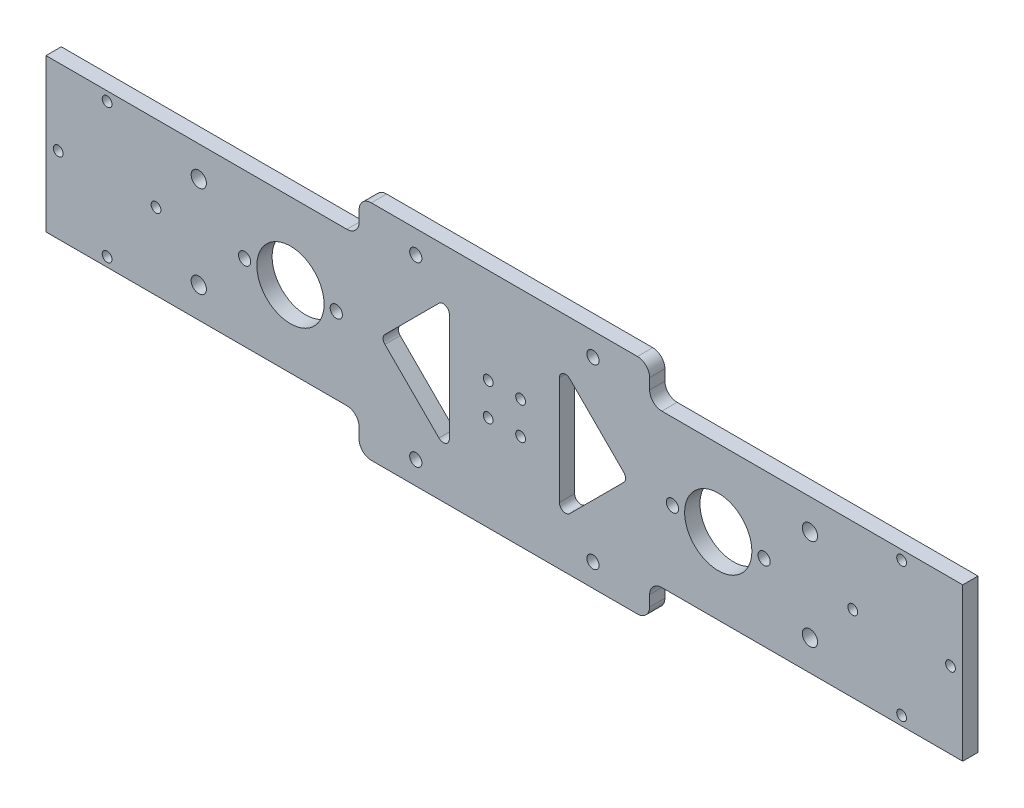
SolidWorks part; units mm, degrees
ref_plane "前视基准面" through (0, 0, 0) normal (0, 0, 1) x (1, 0, 0)
ref_plane "上视基准面" through (0, 0, 0) normal (0, 1, 0) x (1, 0, 0)
ref_plane "右视基准面" through (0, 0, 0) normal (1, 0, 0) x (0, 0, -1)
ref_plane "基准面1" through (0, 0, 0) normal (0, 0, -1) x (-1, 0, 0)
sketch "草图1" plane through (0, 0, 0) normal (0, 0, -1) x (-1, 0, 0)
  line L0 (-26.5, -36.5) -> (26.5, -36.5)
  line L1 (47.5416, -25) -> (150, -25)
  line L2 (150, -25) -> (150, 25)
  line L3 (150, 25) -> (47.5416, 25)
  line L4 (26.5, 36.5) -> (-26.5, 36.5)
  line L5 (-47.5416, 25) -> (-150, 25)
  line L6 (-150, 25) -> (-150, -25)
  line L7 (-150, -25) -> (-47.5416, -25)
  circle A0 centre (-29, 29) radius 2.1
  circle A1 centre (-29, -29) radius 2.1
  circle A2 centre (29, -29) radius 2.1
  circle A3 centre (29, 29) radius 2.1
  arc A4 (-47.5416, -25) -> (-34.9167, -31.9) centre (-47.5416, -40) cw
  arc A5 (-34.9167, -31.9) -> (-26.5, -36.5) centre (-26.5, -26.5) ccw
  arc A6 (26.5, -36.5) -> (34.9167, -31.9) centre (26.5, -26.5) ccw
  arc A7 (34.9167, -31.9) -> (47.5416, -25) centre (47.5416, -40) cw
  arc A8 (47.5416, 25) -> (34.9167, 31.9) centre (47.5416, 40) cw
  arc A9 (34.9167, 31.9) -> (26.5, 36.5) centre (26.5, 26.5) ccw
  arc A10 (-26.5, 36.5) -> (-34.9167, 31.9) centre (-26.5, 26.5) ccw
  arc A11 (-34.9167, 31.9) -> (-47.5416, 25) centre (-47.5416, 40) cw
  circle A12 centre (-54.5, 0) radius 2.1
  circle A13 centre (-114, 0) radius 1.6
  circle A14 centre (-5.3033, 5.3033) radius 1.6
  circle A15 centre (5.3033, 5.3033) radius 1.6
  circle A16 centre (70, 0) radius 11
  circle A17 centre (-85.5, 0) radius 2.1
  circle A18 centre (85.5, 0) radius 2.1
  circle A19 centre (54.5, 0) radius 2.1
  circle A20 centre (-70, 0) radius 11
  circle A21 centre (5.3033, -5.3033) radius 1.6
  circle A22 centre (-5.3033, -5.3033) radius 1.6
  circle A23 centre (114, 0) radius 1.6
  circle A24 centre (146, 0) radius 1.6
  circle A25 centre (130, 22) radius 1.6
  circle A26 centre (130, -22) radius 1.6
  circle A27 centre (-130, -22) radius 1.6
  circle A28 centre (-130, 22) radius 1.6
  circle A29 centre (-146, 0) radius 1.6
  circle A30 centre (100, 15) radius 2.5
  circle A31 centre (-100, 15) radius 2.5
  circle A32 centre (-100, -15) radius 2.5
  circle A33 centre (100, -15) radius 2.5
extrude "凸台-拉伸1" add sketch "草图1" against normal blind 5
sketch "草图2" plane through (0, 0, 5) normal (0, 0, 1) x (1, 0, 0)
  circle A0 centre (-85.5, 0) radius 3.6895
  circle A1 centre (-54.5, 0) radius 3.294
extrude "凸台-拉伸2" add sketch "草图2" against normal blind 5
sketch "草图3" plane through (0, 0, 5) normal (0, 0, 1) x (1, 0, 0)
  circle A0 centre (-85, 0) radius 2
  circle A1 centre (-55, 0) radius 2
  circle A2 centre (-70, 0) radius 11 construction
  dimension "D1" = 15
  dimension "D2" = 15
  dimension "D3" = 4
  dimension "D4" = 4
extrude "切除-拉伸1" cut sketch "草图3" against normal up to next
ref_plane "基准面2" through (0, 0, 0) normal (-1, 0, 0) x (0, 0, 1)
mirror "镜向1" about plane through (0, 0, 0) normal (-1, 0, 0) of "凸台-拉伸2", "切除-拉伸1"
sketch "草图4" plane through (0, 0, 0) normal (0, 0, -1) x (-1, 0, 0)
  circle A0 centre (28.9914, -28.9914) radius 2
  circle A1 centre (-28.9914, 28.9914) radius 2
  circle A4 centre (28.9914, 28.9914) radius 2
  circle A5 centre (-28.9914, -28.9914) radius 2
  point P0 (0, 0)
  point P2 (0, 0)
  dimension "D1" = 4
  dimension "D2" = 4
  dimension "D3" = 4
  dimension "D4" = 4
  dimension "D6" = 41
  dimension "D7" = 41
  dimension "D8" = 41
  dimension "D5" = 41
sketch "草图5" plane through (0, 0, 0) normal (0, 0, -1) x (-1, 0, 0)
  line L0 (26.5, 36.5) -> (-26.5, 36.5) construction
  line L2 (47.5416, 25) -> (47.5416, 36.5)
  line L3 (47.5416, 36.5) -> (21.5189, 36.5)
  line L5 (47.5416, -25) -> (150, -25) construction
  line L7 (-47.5416, 25) -> (-47.5416, 36.5)
  line L8 (-47.5416, 36.5) -> (21.5189, 36.5)
  line L11 (-47.5416, 25) -> (-47.5416, -25)
  line L13 (47.5416, 25) -> (47.5416, -25)
  line L15 (26.5, -36.5) -> (47.5416, -36.5)
  line L18 (47.5416, -36.5) -> (47.5416, -25)
  line L19 (26.5, -36.5) -> (-47.5416, -36.5)
  line L22 (-47.5416, -36.5) -> (-47.5416, -25)
  line L23 (-14.0612, 16.4225) -> (11.4339, 16.4225)
  line L24 (-14.0612, 16.4225) -> (-14.0612, -16.9967)
  line L25 (-14.0612, -16.9967) -> (11.4339, -16.9967)
  line L26 (11.4339, 16.4225) -> (11.4339, -16.9967)
  arc A0 (47.5416, -25) -> (34.9167, -31.9) centre (47.5416, -40) ccw construction
extrude "凸台-拉伸3" add sketch "草图5" against normal blind 5
extrude "切除-拉伸2" cut sketch "草图4" against normal up to next
fillet "圆角1" radius 4 8 edges at (47.5416, -25, 2.5) (47.5416, -36.5, 2.5) (-47.5416, -36.5, 2.5) (-47.5416, -25, 2.5) (-47.5416, 25, 2.5) (-47.5416, 36.5, 2.5) (47.5416, 25, 2.5) (47.5416, 36.5, 2.5)
sketch "草图6" plane through (0, 0, 0) normal (0, 0, -1) x (-1, 0, 0)
  line L0 (-21.4142, 19.0858) -> (-39.0858, 1.4142)
  line L1 (-39.0858, -1.4142) -> (-21.4142, -19.0858)
  line L2 (-18, -17.6716) -> (-18, 17.6716)
  line L3 (0, -2.75) -> (0, 2.75) construction
  line L4 (18, -17.6716) -> (18, 17.6716)
  line L5 (39.0858, -1.4142) -> (21.4142, -19.0858)
  line L6 (21.4142, 19.0858) -> (39.0858, 1.4142)
  arc A0 (-21.4142, -19.0858) -> (-18, -17.6716) centre (-20, -17.6716) ccw
  arc A1 (-39.0858, 1.4142) -> (-39.0858, -1.4142) centre (-37.6716, 0) ccw
  arc A2 (-21.4142, 19.0858) -> (-18, 17.6716) centre (-20, 17.6716) cw
  arc A3 (21.4142, 19.0858) -> (18, 17.6716) centre (20, 17.6716) ccw
  arc A4 (39.0858, 1.4142) -> (39.0858, -1.4142) centre (37.6716, 0) cw
  arc A5 (21.4142, -19.0858) -> (18, -17.6716) centre (20, -17.6716) cw
  point P8 (-18, -22.5)
  point P11 (-40.5, 0)
  point P14 (-18, 22.5)
  point P24 (18, 22.5)
  point P25 (40.5, 0)
  point P26 (18, -22.5)
  dimension "D5" = 2
  dimension "D1" = 18
  dimension "D2" = 45
  dimension "D3" = 45
  dimension "D4" = 0
extrude "切除-拉伸3" cut sketch "草图6" against normal blind 10
